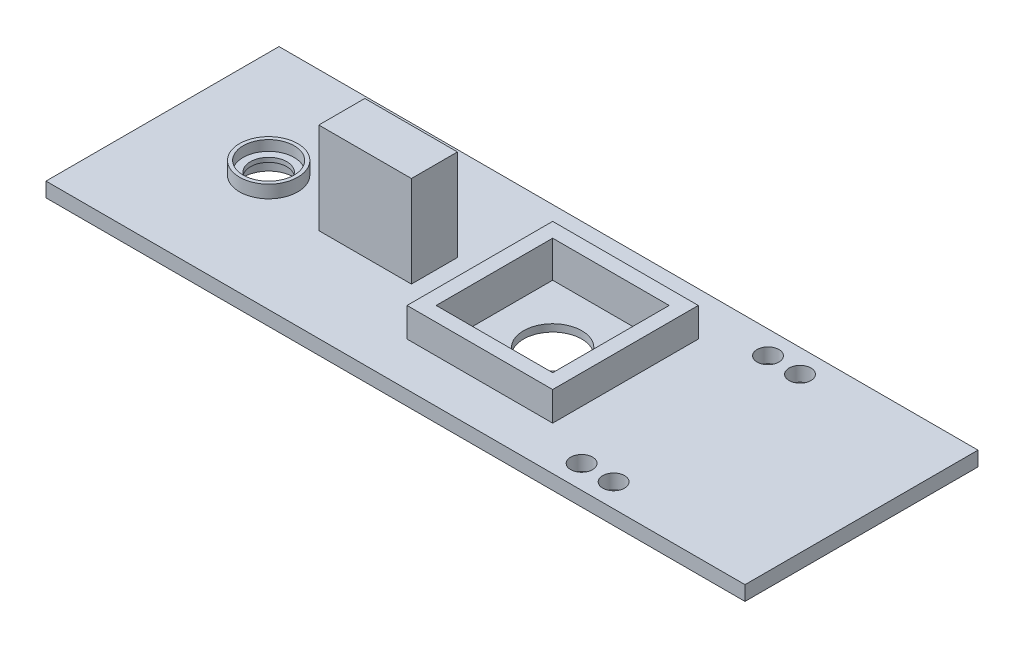
SolidWorks part; units mm, degrees
ref_plane "Front Plane" through (0, 0, 0) normal (0, 0, 1) x (1, 0, 0)
ref_plane "Top Plane" through (0, 0, 0) normal (0, 1, 0) x (1, 0, 0)
ref_plane "Right Plane" through (0, 0, 0) normal (1, 0, 0) x (0, 0, -1)
sketch "Sketch1" plane through (0, 0, 0) normal (0, 1, 0) x (1, 0, 0)
  line L1 (-304.8, -50.8) -> (0, -50.8)
  line L2 (-304.8, -50.8) -> (-304.8, 50.8)
  line L3 (-304.8, 50.8) -> (0, 50.8)
  line L4 (0, -50.8) -> (0, 50.8)
  point P0 (0, 0)
  dimension "D1" = 304.8
  dimension "D2" = 101.6
extrude "Boss-Extrude1" add sketch "Sketch1" along normal blind 6.35
sketch "Sketch2" plane through (0, 6.35, 0) normal (0, 1, 0) x (1, 0, 0)
  circle A0 centre (-258.5106, 0) radius 12.7
extrude "Boss-Extrude3" add sketch "Sketch2" along normal blind 5.5562
sketch "Sketch9" plane through (0, 11.9062, 0) normal (0, 1, 0) x (1, 0, 0)
  circle A0 centre (-258.5106, 0) radius 11.1125
extrude "Cut-Extrude4" cut sketch "Sketch9" against normal blind 4.445
sketch "Sketch10" plane through (0, 0, 0) normal (0, -1, 0) x (-1, 0, 0)
  circle A0 centre (258.5106, 0) radius 11.1125
extrude "Cut-Extrude5" cut sketch "Sketch10" against normal blind 5.5562
sketch "Sketch11" plane through (0, 7.4613, 0) normal (0, 1, 0) x (1, 0, 0)
  circle A0 centre (-258.5106, 0) radius 7.9375
extrude "Cut-Extrude6" cut sketch "Sketch11" against normal through all
sketch "Sketch12" plane through (0, 6.35, 0) normal (0, 1, 0) x (1, 0, 0)
  circle A0 centre (-134.6662, 0) radius 12.7
  dimension "D1" = 25.4
extrude "Cut-Extrude7" cut sketch "Sketch12" against normal through all
sketch "Sketch22" plane through (0, 6.35, 0) normal (0, 1, 0) x (1, 0, 0)
  line L1 (-102.9162, -31.75) -> (-166.4162, -31.75)
  line L2 (-102.9162, -31.75) -> (-102.9162, 31.75)
  line L3 (-102.9162, 31.75) -> (-166.4162, 31.75)
  line L4 (-166.4162, -31.75) -> (-166.4162, 31.75)
  line L5 (-102.9162, -31.75) -> (-166.4162, 31.75) construction
  line L6 (-102.9162, 31.75) -> (-166.4162, -31.75) construction
  circle A0 centre (-134.6662, 0) radius 12.7 construction
  point P0 (-134.6662, 0)
extrude "Boss-Extrude7" add sketch "Sketch22" along normal blind 12.7
sketch "Sketch25" plane through (0, 19.05, 0) normal (0, 1, 0) x (1, 0, 0)
  line L1 (-109.2662, -25.4) -> (-160.0662, -25.4)
  line L2 (-109.2662, -25.4) -> (-109.2662, 25.4)
  line L3 (-109.2662, 25.4) -> (-160.0662, 25.4)
  line L4 (-160.0662, -25.4) -> (-160.0662, 25.4)
  line L5 (-109.2662, -25.4) -> (-160.0662, 25.4) construction
  line L6 (-109.2662, 25.4) -> (-160.0662, -25.4) construction
  circle A0 centre (-134.6662, 0) radius 12.7 construction
  point P0 (-134.6662, 0)
  dimension "D1" = 50.8
  dimension "D2" = 50.8
extrude "Cut-Extrude11" cut sketch "Sketch25" against normal blind 15.875
sketch "Sketch18" plane through (0, 6.35, 0) normal (0, 1, 0) x (1, 0, 0)
  line L2 (-226.612, -10.033) -> (-186.226, -10.033)
  line L3 (-226.612, -10.033) -> (-226.612, 10.033)
  line L4 (-226.612, 10.033) -> (-186.226, 10.033)
  line L5 (-186.226, -10.033) -> (-186.226, 10.033)
extrude "Boss-Extrude5" add sketch "Sketch18" along normal blind 39.878 contours L3 L2 L5 L4
sketch "Sketch32" plane through (0, 6.35, 0) normal (0, 1, 0) x (1, 0, 0)
  line L3 (-304.8, -50.8) -> (0, -50.8) construction
  line L5 (0, 50.8) -> (-304.8, 50.8) construction
  circle A0 centre (-67.442, -40.64) radius 4.7625
  circle A1 centre (-81.412, -40.64) radius 4.7625
  circle A2 centre (-67.442, 40.64) radius 4.7625
  circle A3 centre (-81.412, 40.64) radius 4.7625
  dimension "D1" = 10.16
  dimension "D2" = 10.16
  dimension "D3" = 10.16
  dimension "D4" = 10.16
  dimension "D5" = 13.97
  dimension "D6" = 13.97
  dimension "D7" = 81.28
extrude "Cut-Extrude12" cut sketch "Sketch32" against normal blind 6.35
